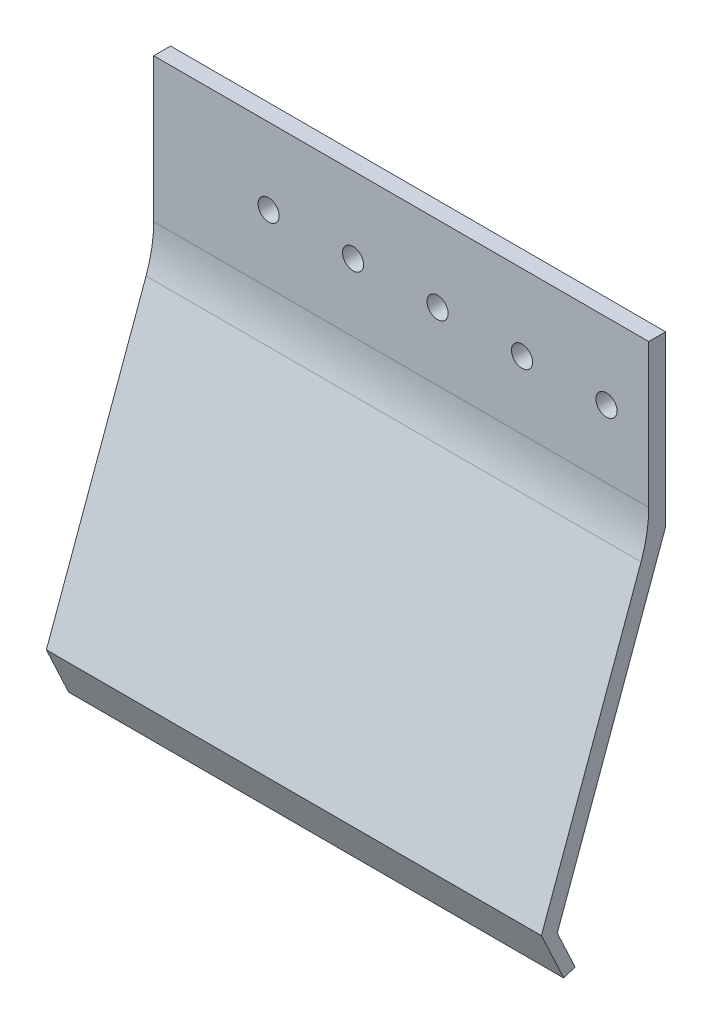
SolidWorks part; units mm, degrees
material "ABS"
ref_plane "Front Plane" through (0, 0, 0) normal (0, 0, 1) x (1, 0, 0)
ref_plane "Top Plane" through (0, 0, 0) normal (0, 1, 0) x (1, 0, 0)
ref_plane "Right Plane" through (0, 0, 0) normal (1, 0, 0) x (0, 0, -1)
sketch "Sketch1" plane through (0, 0, 0) normal (0, 0, 1) x (1, 0, 0)
  line L0 (-72.2, 72.2) -> (37.2, 72.2)
  line L5 (-57.2, 57.2) -> (22.2, 57.2)
  line L6 (-57.2, 57.2) -> (-57.2, -22.2)
  line L7 (-57.2, -22.2) -> (22.2, -22.2)
  line L8 (22.2, 57.2) -> (22.2, -22.2)
  line L9 (37.2, 72.2) -> (37.2, -37.2)
  line L10 (-72.2, -37.2) -> (37.2, -37.2)
  line L11 (-72.2, 72.2) -> (-72.2, -37.2)
  circle A0 centre (-52.5, 52.5) radius 1.5
  circle A1 centre (-17.5, 52.5) radius 1.5
  circle A2 centre (17.5, 52.5) radius 1.5
  circle A3 centre (-52.5, 17.5) radius 1.5
  circle A4 centre (-17.5, 17.5) radius 1.5
  circle A5 centre (17.5, 17.5) radius 1.5
  circle A6 centre (17.5, -17.5) radius 1.5
  circle A7 centre (-17.5, -17.5) radius 1.5
  circle A8 centre (-52.8099, -17.8099) radius 1.5
  circle A9 centre (-35, 35) radius 6
  circle A10 centre (0, 35) radius 6
  circle A11 centre (0, 0) radius 6
  circle A12 centre (-35, 0) radius 6
  point P49 (-17.5, 17.5)
  dimension "D1" = 15
  dimension "D2" = 4
extrude "Boss-Extrude1" add sketch "Sketch1" along normal blind 8 contours L8 L5 L6 L7 A12 A11 A10 A9 A8 A7 A6 A5 A4 A3 A2 A1 A0 | L0 L11 L10 L9 L5 L8 L7 L6
sketch "Sketch2" plane through (37.2, 0, 0) normal (1, 0, 0) x (0, 0, -1)
  line L0 (-8, 72.2) -> (-33.6515, 1.7231)
  line L1 (-153.8845, -135.915) -> (25.507, -52.2634) construction
  line L2 (-8, -37.2) -> (0, -37.2) construction
  line L3 (-8, 72.2) -> (-8, 112.2)
  line L4 (-12, 72.9053) -> (-12, 112.2)
  line L5 (-12, 72.9053) -> (-37.4103, 3.0911)
  line L6 (-37.4103, 3.0911) -> (-32.1276, -8.2377)
  line L7 (-33.6515, 1.7231) -> (-29.4253, -7.34)
  line L8 (-32.1276, -8.2377) -> (-29.4253, -7.34)
  line L9 (-12, 112.2) -> (-8, 112.2)
  dimension "D1" = 25
  dimension "D2" = 45
  dimension "D3" = 75
  dimension "D4" = 40
  dimension "D6" = 12.5
  dimension "D7" = 0
  dimension "D8" = 10
  dimension "D5" = 4
extrude "Boss-Extrude2" add sketch "Sketch2" against normal up to surface (109.4 mm away) separate body up to face at (-72.2, 17.5, 4)
fillet "Fillet1" radius 30 1 edges at (-17.5, 72.9053, 12)
sketch "Sketch3" plane through (37.2, 0, 0) normal (1, 0, 0) x (0, 0, -1)
  line L1 (-8, 72.2) -> (0, 72.2)
  line L2 (-8, 72.2) -> (-8, -37.2)
  line L3 (-8, -37.2) -> (0, -37.2)
  line L4 (0, 72.2) -> (0, -37.2)
sketch "Sketch4" plane through (0, 0, 12) normal (0, 0, 1) x (1, 0, 0)
  line L1 (-72.2, 112.2) -> (37.2, 112.2) construction
  line L2 (-17.5, 112.2) -> (-17.5, 101.2893) construction
  circle A5 centre (-52.8, 94.2) radius 2.5
  circle A6 centre (-32.8, 94.2) radius 2.5
  circle A7 centre (-12.8, 94.2) radius 2.5
  circle A8 centre (7.2, 94.2) radius 2.5
  circle A9 centre (27.2, 94.2) radius 2.5
sketch "Sketch5" plane through (37.2, 0, 0) normal (1, 0, 0) x (0, 0, -1)
  line L1 (0, -37.2) -> (-8, -37.2)
  line L2 (0, -37.2) -> (0, 112.2)
  line L3 (0, 112.2) -> (-8, 112.2)
  line L4 (-8, -37.2) -> (-8, 112.2)
extrude "Boss-Extrude3" add sketch "Sketch5" against normal up to surface (109.4 mm away) up to face at (-72.2, 17.5, 4)
extrude "Cut-Extrude4" cut sketch "Sketch3" against normal blind 135
sketch "Sketch7" plane through (37.2, 0, 0) normal (1, 0, 0) x (0, 0, -1)
  line L1 (-8, 72.2) -> (0, 72.2)
  line L2 (-8, 72.2) -> (-8, 112.2)
  line L3 (-8, 112.2) -> (0, 112.2)
  line L4 (0, 72.2) -> (0, 112.2)
extrude "Cut-Extrude5" cut sketch "Sketch7" against normal blind 135
extrude "Cut-Extrude6" cut sketch "Sketch4" against normal blind 10
sketch "Sketch8" plane through (-72.2, 0, 0) normal (-1, 0, 0) x (0, 0, 1)
  line L8 (12, 112.2) -> (8, 112.2)
  line L9 (8, 112.2) -> (8, 72.2)
  line L10 (8, 72.2) -> (33.6515, 1.7231)
  line L11 (33.6515, 1.7231) -> (29.4253, -7.34)
  line L12 (29.4253, -7.34) -> (32.1276, -8.2377)
  line L13 (32.1276, -8.2377) -> (37.4103, 3.0911)
  line L14 (37.4103, 3.0911) -> (13.8092, 67.9345)
  line L15 (12, 78.1951) -> (12, 112.2)
  line L16 (12, 112.2) -> (8, 112.2)
  line L17 (8, 112.2) -> (8, 72.2)
  line L18 (8, 72.2) -> (33.6515, 1.7231)
  line L19 (33.6515, 1.7231) -> (29.4253, -7.34)
  line L20 (29.4253, -7.34) -> (32.1276, -8.2377)
  line L21 (32.1276, -8.2377) -> (37.4103, 3.0911)
  line L22 (37.4103, 3.0911) -> (13.8092, 67.9345)
  line L23 (12, 78.1951) -> (12, 112.2)
  arc A1 (12, 78.1951) -> (13.8092, 67.9345) centre (42, 78.1951) ccw
  arc A2 (12, 78.1951) -> (13.8092, 67.9345) centre (42, 78.1951) ccw
  dimension "D1" = 0
extrude "Boss-Extrude4" add sketch "Sketch8" along normal blind 7.8
